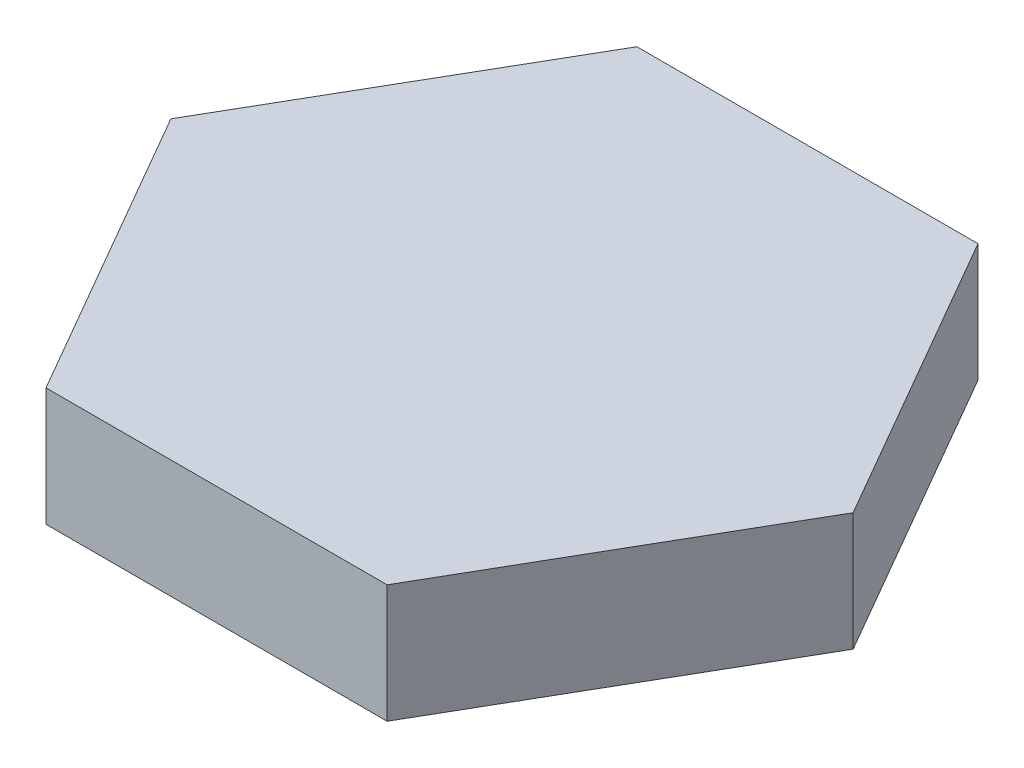
SolidWorks part; units mm, degrees
material "보통 탄소강"
ref_plane "Front" through (0, 0, 0) normal (0, 0, 1) x (1, 0, 0)
ref_plane "Top" through (0, 0, 0) normal (0, 1, 0) x (1, 0, 0)
ref_plane "Right" through (0, 0, 0) normal (1, 0, 0) x (0, 0, -1)
sketch "Sketch1" plane through (0, 0, 0) normal (0, 1, 0) x (1, 0, 0)
  line L1 (-14.4338, 25) -> (-28.8675, 0)
  line L2 (-28.8675, 0) -> (-14.4338, -25)
  line L3 (-14.4338, -25) -> (14.4338, -25)
  line L4 (14.4338, -25) -> (28.8675, 0)
  line L5 (28.8675, 0) -> (14.4338, 25)
  line L6 (14.4338, 25) -> (-14.4338, 25)
  circle A0 centre (0, 0) radius 25 construction
  dimension "D1" = 50
extrude "Extrude1" add sketch "Sketch1" along normal blind 10
equation "\"D\" = 50mm"
equation "\"H\" = 10mm"
equation "\"D1@Sketch1\"= \"D\""
equation "\"D1@Extrude1\"= \"H\""
